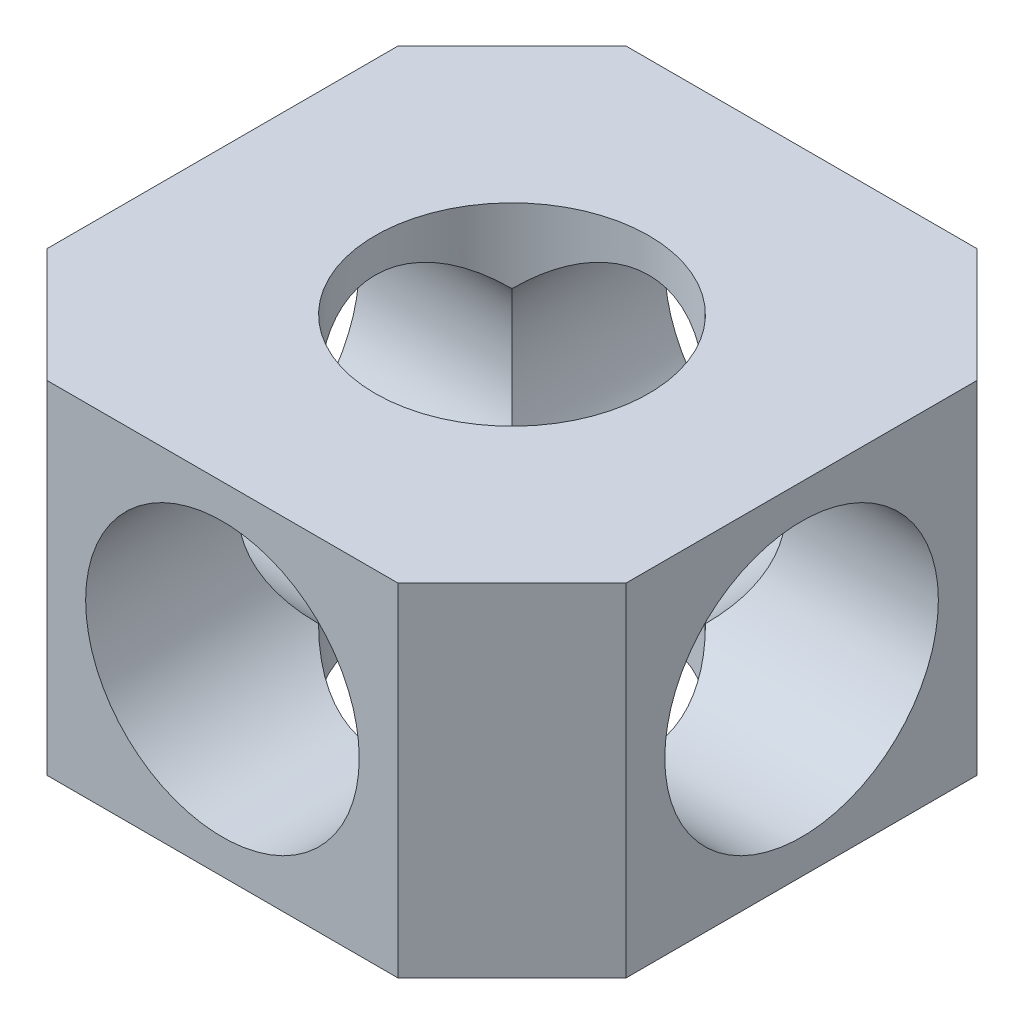
SolidWorks part; units mm, degrees
ref_plane "Front Plane" through (0, 0, 0) normal (0, 0, 1) x (1, 0, 0)
ref_plane "Top Plane" through (0, 0, 0) normal (0, 1, 0) x (1, 0, 0)
ref_plane "Right Plane" through (0, 0, 0) normal (1, 0, 0) x (0, 0, -1)
sketch "Sketch1" plane through (0, 0, 0) normal (0, 1, 0) x (1, 0, 0)
  line L1 (-12.7, 12.7) -> (12.7, 12.7)
  line L2 (-12.7, 12.7) -> (-12.7, -12.7)
  line L3 (-12.7, -12.7) -> (12.7, -12.7)
  line L4 (12.7, 12.7) -> (12.7, -12.7)
  line L5 (-12.7, 12.7) -> (12.7, -12.7) construction
  line L6 (-12.7, -12.7) -> (12.7, 12.7) construction
  point P0 (0, 0)
  dimension "D1" = 25.4
extrude "Boss-Extrude1" add sketch "Sketch1" along normal mid plane 15
chamfer "Chamfer1" distance 5 4 edges at (12.7, 0, 12.7) (12.7, 0, -12.7) (-12.7, 0, -12.7) (-12.7, 0, 12.7)
sketch "Sketch2" plane through (0, 7.5, 0) normal (0, 1, 0) x (1, 0, 0)
  circle A0 centre (0, 0) radius 6
  dimension "D1" = 12
extrude "Cut-Extrude1" cut sketch "Sketch2" against normal through all
sketch "Sketch3" plane through (-12.7, 0, 0) normal (-1, 0, 0) x (0, 0, 1)
  circle A0 centre (0, 0) radius 6
  dimension "D1" = 12
extrude "Cut-Extrude2" cut sketch "Sketch3" against normal through all
pattern_circular "CirPattern7" count 2 over 90 about axis through (0, -7.5, 0) along (0, 1, 0) of "Cut-Extrude2"
